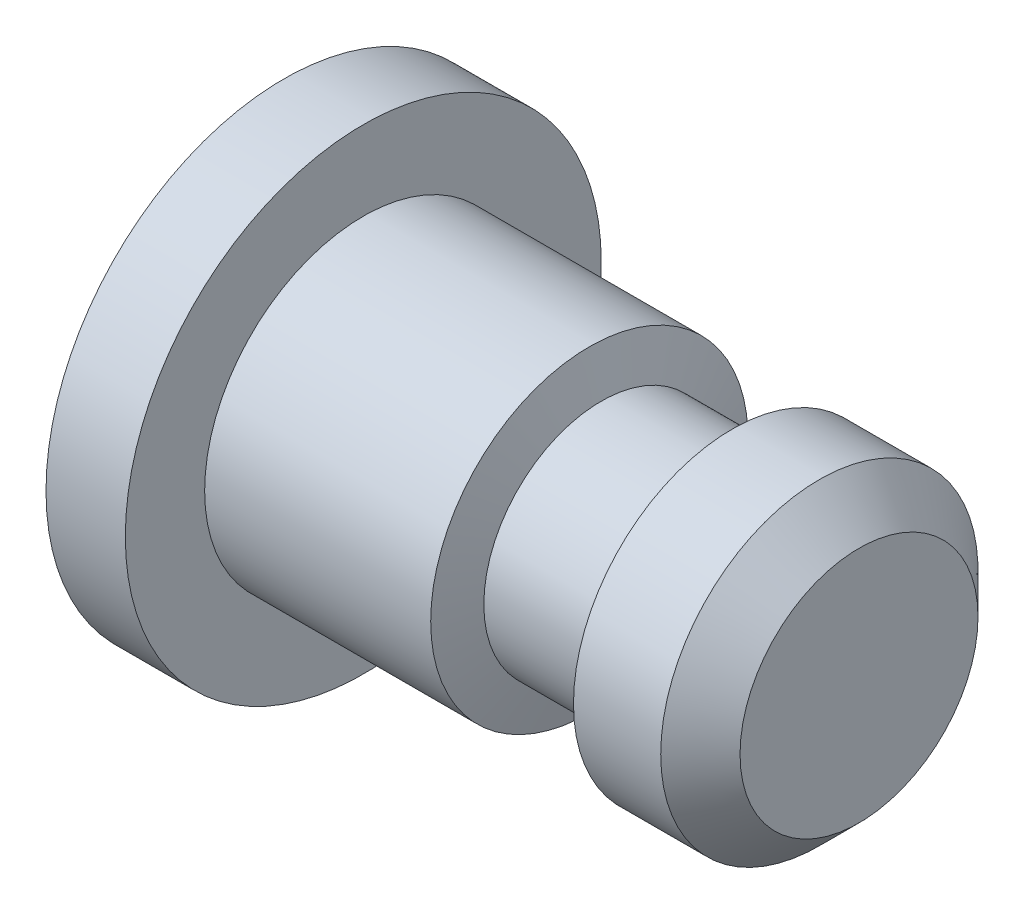
SolidWorks part; units mm, degrees
ref_plane "Front Plane" through (0, 0, 0) normal (0, 0, 1) x (1, 0, 0)
ref_plane "Top Plane" through (0, 0, 0) normal (0, 1, 0) x (1, 0, 0)
ref_plane "Right Plane" through (0, 0, 0) normal (1, 0, 0) x (0, 0, -1)
sketch "Sketch1" plane through (0, 0, 0) normal (0, 0, 1) x (1, 0, 0)
  line L0 (0, 6) -> (0, 0)
  line L1 (0, 0) -> (14.5, 0)
  line L2 (14.5, 0) -> (14.5, 4)
  line L3 (14.5, 4) -> (11.3, 4)
  line L4 (11.3, 4) -> (11, 2.9606)
  line L5 (11, 2.9606) -> (8, 2.9606)
  line L6 (8, 2.9606) -> (7.7, 4)
  line L7 (7.7, 4) -> (2, 4)
  line L8 (2, 4) -> (2, 6)
  line L9 (2, 6) -> (0, 6)
  point P2 (16.0316, 1.8422)
  point P3 (18.8962, 3.4872)
  point P12 (10.7562, 3.5439)
  point P13 (7.6363, 1.7854)
  point P15 (4.403, 3.005)
  point P16 (0, 0)
  point P17 (7.2392, 1.7854)
  point P18 (10.7562, 2.8065)
  point P19 (1.2392, 2.8632)
  point P20 (0, 0)
  dimension "D1" = 14.5
  dimension "D2" = 6
  dimension "D3" = 3
  dimension "D4" = 5.7
  dimension "D5" = 3.6
  dimension "D6" = 12.5
  dimension "D7" = 4
revolve "Revolve1" add sketch "Sketch1" angle 360 about L1
chamfer "Chamfer1" distance 1 angle 45 1 edges at (14.5, 0, 4)
